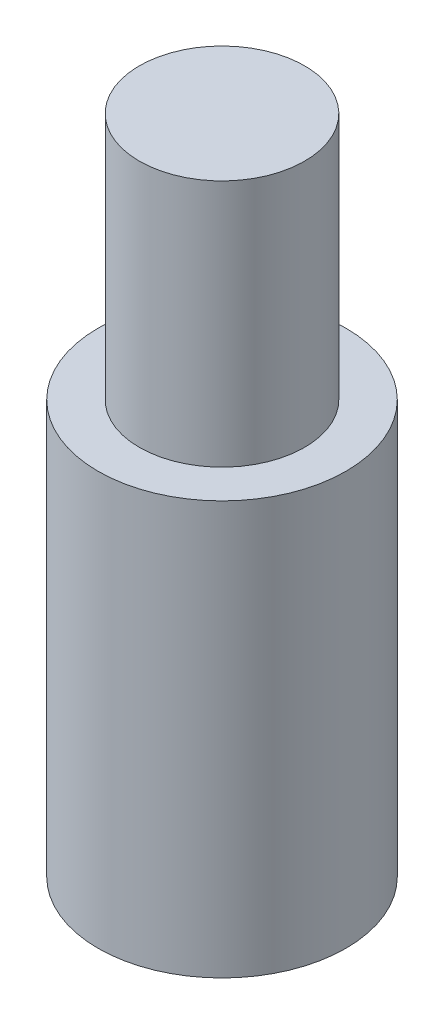
SolidWorks part; units mm, degrees
material "AISI 1010 Aço, barra laminada a quente"
ref_plane "Plano frontal" through (0, 0, 0) normal (0, 0, 1) x (1, 0, 0)
ref_plane "Plano superior" through (0, 0, 0) normal (0, 1, 0) x (1, 0, 0)
ref_plane "Plano direito" through (0, 0, 0) normal (1, 0, 0) x (0, 0, -1)
sketch "Esboço1" plane through (0, 0, 0) normal (0, 1, 0) x (1, 0, 0)
  circle A0 centre (0, 0) radius 15
  dimension "D1" = 30
extrude "Ressalto-extrusão1" add sketch "Esboço1" along normal blind 50
sketch "Esboço2" plane through (0, 50, 0) normal (0, 1, 0) x (1, 0, 0)
  circle A0 centre (0, 0) radius 10
  dimension "D1" = 20
extrude "Ressalto-extrusão2" add sketch "Esboço2" along normal blind 30
